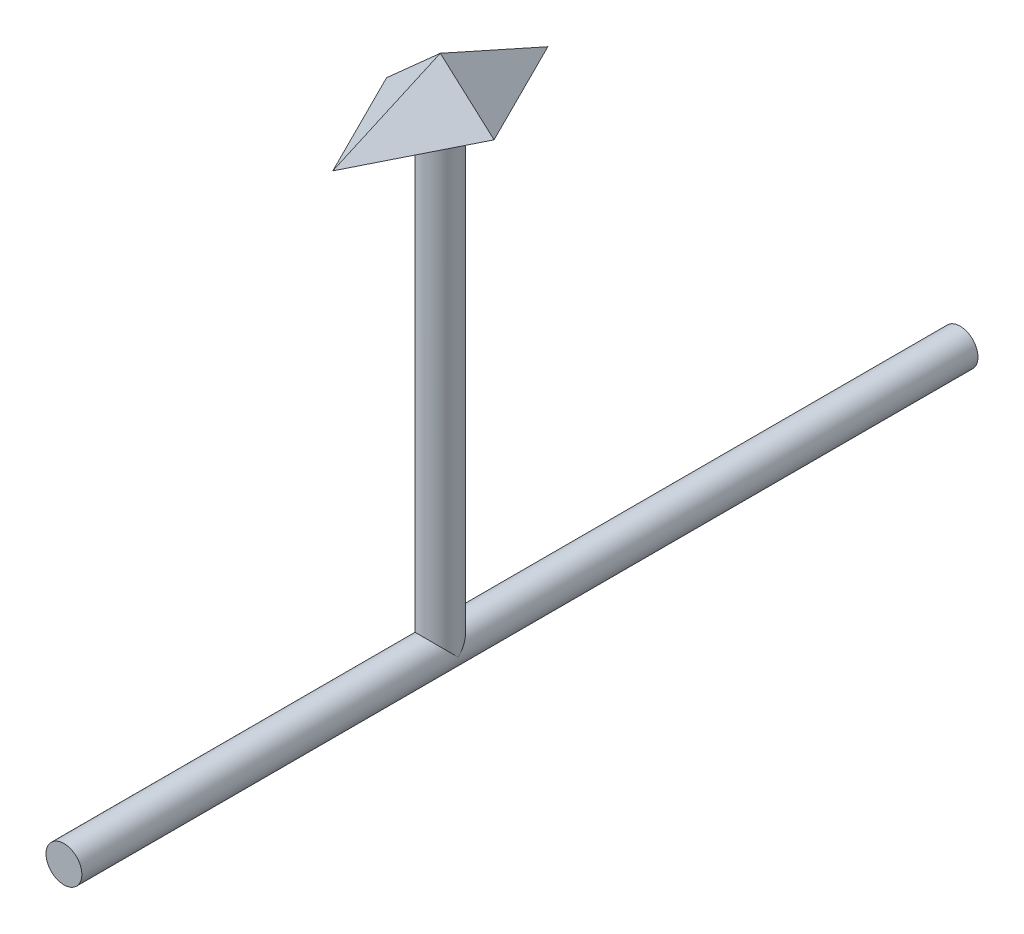
SolidWorks part; units mm, degrees
ref_plane "Front Plane" through (0, 0, 0) normal (0, 0, 1) x (1, 0, 0)
ref_plane "Top Plane" through (0, 0, 0) normal (0, 1, 0) x (1, 0, 0)
ref_plane "Right Plane" through (0, 0, 0) normal (1, 0, 0) x (0, 0, -1)
sketch "Sketch1" plane through (0, 0, 0) normal (0, 0, 1) x (1, 0, 0)
  circle A0 centre (0, 0) radius 5
  dimension "D1" = 10
extrude "Boss-Extrude1" add sketch "Sketch1" along normal blind 600
sketch "Sketch2" plane through (0, 0, 0) normal (0, 1, 0) x (1, 0, 0)
  circle A0 centre (0, -145) radius 5
  dimension "D1" = 10
  dimension "D2" = 145
extrude "Boss-Extrude2" add sketch "Sketch2" along normal blind 130
sketch "Sketch4" plane through (0, 130, 0) normal (0, 1, 0) x (1, 0, 0)
  line L1 (0, -115) -> (0, -175) construction
  line L3 (-15, -145) -> (15, -145) construction
  line L4 (0, -115) -> (-15, -145)
  line L5 (-15, -145) -> (0, -175)
  line L6 (0, -115) -> (15, -145)
  line L7 (15, -145) -> (0, -175)
  point P1 (0, -145)
  dimension "D1" = 60
  dimension "D2" = 30
extrude "Boss-Extrude3" add sketch "Sketch4" along normal blind 130 draft 45
sketch "Sketch5" plane through (0, 0, 0) normal (1, 0, 0) x (0, 0, -1)
  circle A0 centre (-355, 0) radius 5
  dimension "D1" = 10
  dimension "D2" = 355
extrude "Boss-Extrude4" add sketch "Sketch5" along normal blind 130
sketch "Sketch6" plane through (130, 0, 0) normal (1, 0, 0) x (0, 0, -1)
  line L0 (-355, 15) -> (-355, -15) construction
  line L1 (-385, 0) -> (-325, 0) construction
  line L2 (-355, 15) -> (-385, 0)
  line L3 (-385, 0) -> (-355, -15)
  line L4 (-355, 15) -> (-325, 0)
  line L5 (-325, 0) -> (-355, -15)
  point P1 (-355, 0)
  dimension "D1" = 30
  dimension "D2" = 60
extrude "Boss-Extrude5" add sketch "Sketch6" along normal blind 130 draft 45
sketch "Sketch7" plane through (0, 0, 0) normal (0, 1, 0) x (1, 0, 0)
  line L1 (-268.6165, -250) -> (268.6165, -250)
  line L2 (-268.6165, -250) -> (-268.6165, -750)
  line L3 (-268.6165, -750) -> (268.6165, -750)
  line L4 (268.6165, -250) -> (268.6165, -750)
  line L5 (-268.6165, -250) -> (268.6165, -750) construction
  line L6 (-268.6165, -750) -> (268.6165, -250) construction
  point P0 (0, -500)
  point P5 (0, 0)
  point P6 (268.6165, -638.0138)
  dimension "D1" = 250
  dimension "D2" = 500
extrude "Cut-Extrude1" cut sketch "Sketch7" against normal mid plane 200
